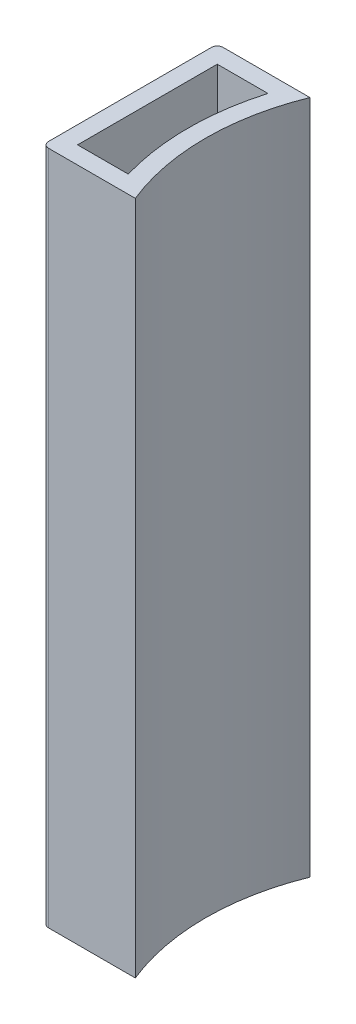
SolidWorks part; units mm, degrees
ref_plane "Front Plane" through (0, 0, 0) normal (0, 0, 1) x (1, 0, 0)
ref_plane "Top Plane" through (0, 0, 0) normal (0, 1, 0) x (1, 0, 0)
ref_plane "Right Plane" through (0, 0, 0) normal (1, 0, 0) x (0, 0, -1)
sketch "Sketch1" plane through (0, 0, 0) normal (0, 1, 0) x (1, 0, 0)
  line L0 (15.919, 0) -> (15.92, 0)
  line L1 (0, 0) -> (0, -30)
  line L2 (0, -30) -> (15.92, -30)
  line L3 (15.92, 0) -> (15.919, 0) construction
  line L4 (15.919, 0) -> (15.92, 0)
  line L5 (0, 0) -> (15.919, 0)
  arc A0 (15.919, 0) -> (15.919, -30) centre (53, -15) ccw
  dimension "D1" = 15.92
extrude "Boss-Extrude1" add sketch "Sketch1" along normal blind 116 contours A0 L5 L1 L2
shell "Shell1" thickness 3
fillet "Fillet1" radius 1 2 edges at (0, 58, 30) (0, 58, 0)
sketch "Sketch2" plane through (0, 0, 0) normal (-1, 0, 0) x (0, 0, 1)
  line L0 (15, 116) -> (15, 0) construction
  line L1 (1, 116) -> (29, 116) construction
  line L2 (1, 0) -> (29, 0) construction
  line L3 (0, 20) -> (30, 20) construction
  line L4 (0, 0) -> (0, 116) construction
  line L5 (30, 116) -> (30, 0) construction
  line L6 (0, 96) -> (30, 96) construction
  line L7 (15, 96) -> (15, 20) construction
  line L8 (19, 96) -> (19, 20)
  line L9 (11, 96) -> (11, 20)
  arc A0 (19, 96) -> (11, 96) centre (15, 96) ccw
  arc A1 (11, 20) -> (19, 20) centre (15, 20) ccw
  point P16 (15, 58)
  dimension "D1" = 20
  dimension "D2" = 20
extrude "Cut-Extrude1" cut sketch "Sketch2" against normal up to vertex (3 mm away)
